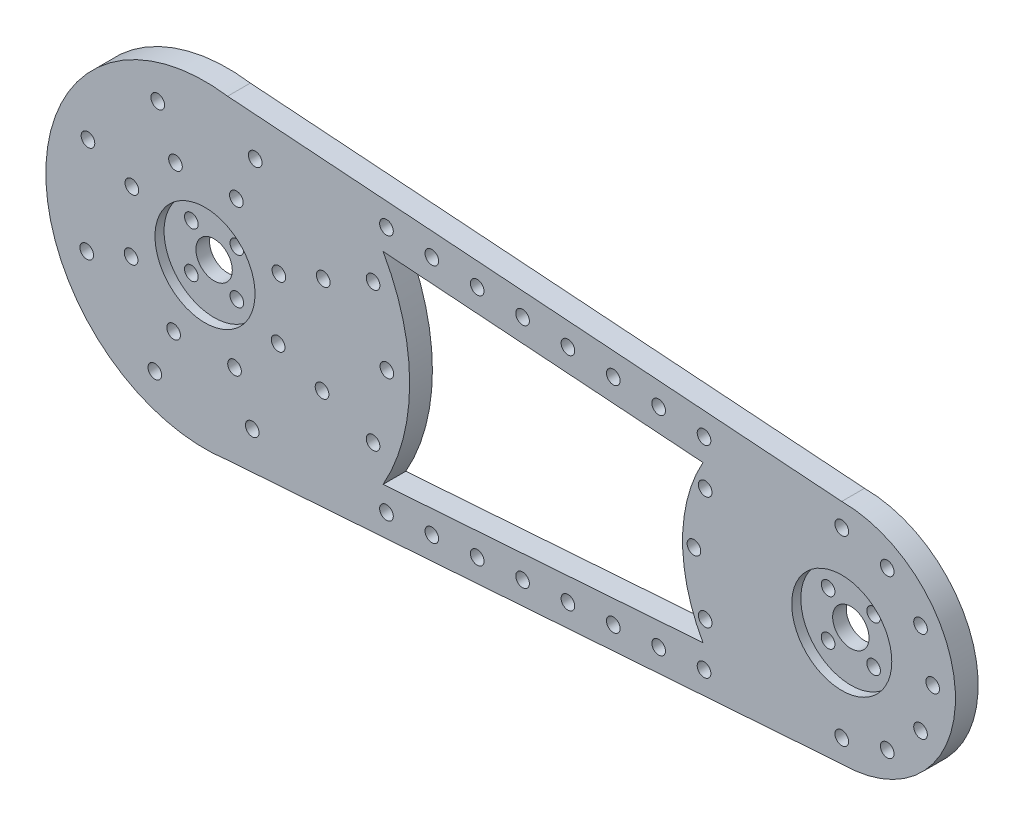
SolidWorks part; units mm, degrees
ref_plane "前视基准面" through (0, 0, 0) normal (0, 0, 1) x (1, 0, 0)
ref_plane "上视基准面" through (0, 0, 0) normal (0, 1, 0) x (1, 0, 0)
ref_plane "右视基准面" through (0, 0, 0) normal (1, 0, 0) x (0, 0, -1)
other "Configuration Table"
sketch "草图1" plane through (0, 0, 0) normal (0, 0, 1) x (1, 0, 0)
  line L0 (0, 0) -> (140, 0)
  line L1 (0, 35) -> (140, 25)
  line L2 (0, -35) -> (140, -25)
  circle A0 centre (0, 0) radius 35
  circle A1 centre (140, 0) radius 25
  dimension "D1" = 70
  dimension "D3" = 50
  dimension "D2" = 140
extrude "凸台-拉伸3" add sketch "草图1" along normal blind 5
sketch "草图4" plane through (0, 0, 5) normal (0, 0, 1) x (1, 0, 0)
  line L1 (-5, -5) -> (5, -5)
  line L2 (-5, -5) -> (-5, 5)
  line L3 (-5, 5) -> (5, 5)
  line L4 (5, -5) -> (5, 5)
  line L5 (-5, -5) -> (5, 5) construction
  line L6 (-5, 5) -> (5, -5) construction
  line L7 (135, -5) -> (145, -5)
  line L8 (135, -5) -> (135, 5)
  line L9 (135, 5) -> (145, 5)
  line L10 (145, -5) -> (145, 5)
  line L11 (135, -5) -> (145, 5) construction
  line L12 (135, 5) -> (145, -5) construction
  circle A0 centre (0, 0) radius 4
  circle A1 centre (-5, 5) radius 1.5
  circle A2 centre (5, 5) radius 1.5
  circle A3 centre (5, -5) radius 1.5
  circle A4 centre (-5, -5) radius 1.5
  circle A5 centre (140, 0) radius 4
  circle A6 centre (135, 5) radius 1.5
  circle A7 centre (145, 5) radius 1.5
  circle A8 centre (145, -5) radius 1.5
  circle A9 centre (135, -5) radius 1.5
  dimension "D1" = 8
  dimension "D4" = 3
  dimension "D6" = 8
  dimension "D9" = 3
  dimension "D2" = 10
  dimension "D3" = 10
  dimension "D7" = 10
  dimension "D8" = 10
  dimension "D5" = 4
  dimension "D10" = 4
extrude "切除-拉伸3" cut sketch "草图4" against normal blind 5 contours A5 | A0 | L2 A4 L1 | L1 A4 L2 | A6 | A9 | A8 | A7 | A1 | A2 | A3
sketch "草图5" plane through (0, 0, 5) normal (0, 0, 1) x (1, 0, 0)
  circle A0 centre (0, 0) radius 11
  circle A1 centre (140, 0) radius 11
  dimension "D1" = 22
  dimension "D2" = 22
extrude "切除-拉伸4" cut sketch "草图5" against normal blind 2
sketch "草图6" plane through (0, 0, 5) normal (0, 0, 1) x (1, 0, 0)
  circle A0 centre (0, 0) radius 30
  circle A1 centre (0, 30) radius 1.5
  circle A2 centre (15, 25.9808) radius 1.5
  circle A3 centre (25.9808, 15) radius 1.5
  circle A4 centre (30, 0) radius 1.5
  circle A5 centre (25.9808, -15) radius 1.5
  circle A6 centre (15, -25.9808) radius 1.5
  circle A7 centre (0, -30) radius 1.5
  circle A8 centre (-15, -25.9808) radius 1.5
  circle A9 centre (-25.9808, -15) radius 1.5
  circle A10 centre (-30, 0) radius 1.5
  circle A11 centre (-25.9808, 15) radius 1.5
  circle A12 centre (-15, 25.9808) radius 1.5
  circle A13 centre (140, 0) radius 20
  circle A14 centre (140, 20) radius 1.5
  circle A15 centre (150, 17.3205) radius 1.5
  circle A16 centre (157.3205, 10) radius 1.5
  circle A17 centre (160, 0) radius 1.5
  circle A18 centre (157.3205, -10) radius 1.5
  circle A19 centre (150, -17.3205) radius 1.5
  circle A20 centre (140, -20) radius 1.5
  circle A21 centre (130, -17.3205) radius 1.5
  circle A22 centre (122.6795, -10) radius 1.5
  circle A23 centre (120, 0) radius 1.5
  circle A24 centre (122.6795, 10) radius 1.5
  circle A25 centre (130, 17.3205) radius 1.5
  point P29 (0, 0)
  dimension "D1" = 60
  dimension "D2" = 3
  dimension "D4" = 40
  dimension "D5" = 3
  dimension "D3" = 12
  dimension "D6" = 12
extrude "切除-拉伸6" cut sketch "草图6" against normal through all contours A0 A12 | A11 | A1 | A2 | A3 | A4 | A5 | A6 | A7 | A8 | A9 | A10 | A25 | A14 | A15 | A16 | A17 | A18 | A19 | A20 | A21 | A22 | A23 | A24
sketch "草图8" plane through (0, 0, 5) normal (0, 0, 1) x (1, 0, 0)
  line L4 (-0.1715, -29.9995) -> (139.8316, -19.9993)
  line L5 (139.8316, 19.9993) -> (-0.1715, 29.9995)
  line L6 (-0.1715, -29.9995) -> (139.8316, -19.9993)
  line L7 (139.8316, 19.9993) -> (-0.1715, 29.9995)
  line L8 (-0.7125, 25.0254) -> (139.2875, 15.0254)
  line L9 (-0.7125, 25.0254) -> (139.2875, 15.0254)
  line L11 (-0.7125, -25.0254) -> (139.2875, -15.0254)
  line L12 (-0.7125, -25.0254) -> (139.2875, -15.0254)
  circle A3 centre (0, 30) radius 1.5
  arc A4 (139.8316, -19.9993) -> (139.8316, 19.9993) centre (140, 0) ccw
  arc A5 (-0.1715, 29.9995) -> (-0.1715, -29.9995) centre (0, 0) ccw
  arc A6 (139.8316, -19.9993) -> (139.8316, 19.9993) centre (140, 0) ccw
  arc A7 (-0.1715, 29.9995) -> (-0.1715, -29.9995) centre (0, 0) ccw
  circle A8 centre (9.9746, 29.2875) radius 1.5
  circle A9 centre (19.9492, 28.5751) radius 1.5
  circle A10 centre (29.9238, 27.8626) radius 1.5
  circle A11 centre (39.8983, 27.1501) radius 1.5
  circle A12 centre (49.8729, 26.4376) radius 1.5
  circle A13 centre (59.8475, 25.7252) radius 1.5
  circle A14 centre (69.8221, 25.0127) radius 1.5
  circle A15 centre (79.7967, 24.3002) radius 1.5
  circle A16 centre (89.7713, 23.5878) radius 1.5
  circle A17 centre (99.7459, 22.8753) radius 1.5
  circle A18 centre (109.7205, 22.1628) radius 1.5
  circle A19 centre (119.695, 21.4504) radius 1.5
  circle A20 centre (129.6696, 20.7379) radius 1.5
  circle A21 centre (0, -30) radius 1.5
  circle A22 centre (9.9746, -29.2875) radius 1.5
  circle A23 centre (19.9492, -28.5751) radius 1.5
  circle A24 centre (29.9238, -27.8626) radius 1.5
  circle A25 centre (39.8983, -27.1501) radius 1.5
  circle A26 centre (49.8729, -26.4376) radius 1.5
  circle A27 centre (59.8475, -25.7252) radius 1.5
  circle A28 centre (69.8221, -25.0127) radius 1.5
  circle A29 centre (79.7967, -24.3002) radius 1.5
  circle A30 centre (89.7713, -23.5878) radius 1.5
  circle A31 centre (99.7459, -22.8753) radius 1.5
  circle A32 centre (109.7205, -22.1628) radius 1.5
  circle A33 centre (119.695, -21.4504) radius 1.5
  circle A34 centre (129.6696, -20.7379) radius 1.5
  circle A35 centre (0, 0) radius 35
  circle A36 centre (140, 0) radius 25
  dimension "D2" = 14
  dimension "D1" = 5
  dimension "D4" = 10
  dimension "D5" = 10
  dimension "D3" = 14
extrude "切除-拉伸8" cut sketch "草图8" against normal through all contours A36 L9 A35 L12 | L6 A25 | L6 A25 | A8 | A9 | A10 | A11 | A12 | A13 | A14 | A16 | A15 | A17 | A18 | A19 | A20 | A34 | A33 | A32 | A31 | A30 | A29 | A28 | A27 | A26 | A24 | A23 | A22
sketch "草图9" plane through (0, 0, 5) normal (0, 0, 1) x (1, 0, 0)
  circle A0 centre (15, 25.9808) radius 1.5
  circle A1 centre (15, -25.9808) radius 1.5
extrude "凸台-拉伸4" add sketch "草图9" against normal blind 5
sketch "草图10" plane through (0, 0, 5) normal (0, 0, 1) x (1, 0, 0)
  circle A0 centre (130, -17.3205) radius 1.5
  circle A1 centre (130, 17.3205) radius 1.5
extrude "凸台-拉伸6" add sketch "草图10" against normal blind 5
sketch "草图11" plane through (0, 0, 5) normal (0, 0, 1) x (1, 0, 0)
  circle A0 centre (25.9808, -15) radius 1.5
  circle A1 centre (30, 0) radius 1.5
  circle A2 centre (25.9808, 15) radius 1.5
  circle A3 centre (122.6795, -10) radius 1.5
  circle A4 centre (120, 0) radius 1.5
  circle A5 centre (122.6795, 10) radius 1.5
  circle A6 centre (119.695, 21.4504) radius 1.5
  circle A7 centre (119.695, -21.4504) radius 1.5
  circle A8 centre (29.9238, -27.8626) radius 1.5
  circle A9 centre (29.9238, 27.8626) radius 1.5
  circle A10 centre (0, 0) radius 11
  circle A11 centre (0, 0) radius 35
  circle A12 centre (19.9492, -28.5751) radius 1.5
  circle A13 centre (19.9492, 28.5751) radius 1.5
  circle A14 centre (140, 0) radius 11
  circle A15 centre (140, 0) radius 24.9365
  circle A16 centre (129.6696, -20.7379) radius 1.5
  circle A17 centre (129.6696, 20.7379) radius 1.5
extrude "凸台-拉伸12" add sketch "草图11" against normal blind 5 contours A16 | A7 | A6 | A13 A11 A12 A0 A1 A2 A10 | A1 | A2 | A11 A13 | A11 A13 | A9 | A8 | A17
sketch "草图14" plane through (0, 0, 0) normal (0, 0, -1) x (-1, 0, 0)
  circle A2 centre (-11.0396, 25.7318) radius 1.5
  circle A3 centre (-6.8997, 16.0824) radius 1.5
  circle A4 centre (6.4931, 16.2508) radius 1.5
  circle A5 centre (10.389, 26.0013) radius 1.5
  circle A6 centre (16.0824, 6.8997) radius 1.5
  circle A7 centre (25.7318, 11.0396) radius 1.5
  circle A8 centre (16.2508, -6.4931) radius 1.5
  circle A9 centre (26.0013, -10.389) radius 1.5
  circle A10 centre (6.8997, -16.0824) radius 1.5
  circle A11 centre (11.0396, -25.7318) radius 1.5
  circle A12 centre (-6.4931, -16.2508) radius 1.5
  circle A13 centre (-10.389, -26.0013) radius 1.5
  circle A14 centre (-16.0824, -6.8997) radius 1.5
  circle A15 centre (-25.7318, -11.0396) radius 1.5
  circle A16 centre (-16.2508, 6.4931) radius 1.5
  circle A17 centre (-26.0013, 10.389) radius 1.5
  point P41 (0, 0)
  dimension "D1" = 8
extrude "切除-拉伸9" cut sketch "草图14" against normal blind 5
sketch "草图15" plane through (0, 0, 0) normal (0, 0, -1) x (-1, 0, 0)
  line L0 (-26.2977, -23.0961) -> (-32.9913, -22.618)
  line L1 (-26.2977, -23.0961) -> (-121.0676, -16.3268) construction
  line L2 (-26.2977, 23.0961) -> (-32.9913, 22.618)
  line L3 (-26.2977, 23.0961) -> (-121.0676, 16.3268) construction
  circle A0 centre (0, 0) radius 35
  circle A1 centre (0, 0) radius 40
  dimension "D1" = 80
extrude "凸台-拉伸13" add sketch "草图15" against normal blind 5 contours L2 A1 L0 A0
sketch "草图16" plane through (0, 0, 0) normal (0, 0, -1) x (-1, 0, 0)
  circle A1 centre (-35, 0) radius 1.5
  circle A2 centre (-32.3358, 13.3939) radius 1.5
  circle A16 centre (-32.3358, -13.3939) radius 1.5
  circle A17 centre (-24.7487, 24.7487) radius 1.5 [skipped]
  circle A18 centre (-24.7487, -24.7487) radius 1.5 [skipped]
  circle A19 centre (-13.3939, -32.3358) radius 1.5 [skipped]
  circle A20 centre (-13.3939, 32.3358) radius 1.5 [skipped]
  circle A21 centre (0, 35) radius 1.5 [skipped]
  circle A22 centre (13.3939, 32.3358) radius 1.5 [skipped]
  circle A23 centre (24.7487, 24.7487) radius 1.5 [skipped]
  circle A24 centre (32.3358, 13.3939) radius 1.5 [skipped]
  circle A25 centre (35, 0) radius 1.5 [skipped]
  circle A26 centre (32.3358, -13.3939) radius 1.5 [skipped]
  circle A27 centre (24.7487, -24.7487) radius 1.5 [skipped]
  circle A28 centre (13.3939, -32.3358) radius 1.5 [skipped]
  circle A29 centre (0, -35) radius 1.5 [skipped]
  dimension "D1" = 3
  dimension "D2" = 16
extrude "切除-拉伸10" cut sketch "草图16" against normal blind 5
sketch "草图18" plane through (0, 0, 5) normal (0, 0, 1) x (1, 0, 0)
  line L0 (32.9913, 22.618) -> (39.1555, 22.1777)
  line L1 (32.9913, 22.618) -> (121.0676, 16.3268) construction
  line L2 (32.9913, -22.618) -> (39.1555, -22.1777)
  line L3 (32.9913, -22.618) -> (121.0676, -16.3268) construction
  circle A0 centre (0, 0) radius 40
  circle A1 centre (0, 0) radius 45
  dimension "D1" = 90
extrude "凸台-拉伸14" add sketch "草图18" against normal blind 5 contours L2 A1 L0 A0
sketch "草图19" plane through (0, 0, 5) normal (0, 0, 1) x (1, 0, 0)
  circle A0 centre (32.3358, 13.3939) radius 1.5
  circle A1 centre (35, 0) radius 1.5
  circle A2 centre (32.3358, -13.3939) radius 1.5
extrude "凸台-拉伸15" add sketch "草图19" against normal blind 5
sketch "草图20" plane through (0, 0, 0) normal (0, 0, -1) x (-1, 0, 0)
  circle A1 centre (-40, 0) radius 1.5
  circle A2 centre (-36.9552, 15.3073) radius 1.5
  circle A4 centre (-15.3073, 36.9552) radius 1.5
  circle A5 centre (0, 40) radius 1.5
  circle A6 centre (15.3073, 36.9552) radius 1.5
  circle A7 centre (28.2843, 28.2843) radius 1.5
  circle A8 centre (36.9552, 15.3073) radius 1.5
  circle A9 centre (40, 0) radius 1.5
  circle A10 centre (36.9552, -15.3073) radius 1.5
  circle A11 centre (28.2843, -28.2843) radius 1.5
  circle A12 centre (15.3073, -36.9552) radius 1.5
  circle A13 centre (0, -40) radius 1.5
  circle A14 centre (-15.3073, -36.9552) radius 1.5
  circle A16 centre (-36.9552, -15.3073) radius 1.5
  circle A17 centre (-28.2843, -28.2843) radius 1.5 [skipped]
  circle A18 centre (-28.2843, 28.2843) radius 1.5 [skipped]
  point P38 (0, 0)
  dimension "D2" = 3
  dimension "D3" = 16
extrude "切除-拉伸11" cut sketch "草图20" against normal blind 5
sketch "草图21" plane through (0, 0, 0) normal (0, 0, -1) x (-1, 0, 0)
  line L0 (-121.0676, 16.3268) -> (-115.113, 16.7522)
  line L1 (-39.1555, 22.1777) -> (-121.0676, 16.3268) construction
  line L2 (-121.0676, -16.3268) -> (-115.113, -16.7522)
  line L3 (-39.1555, -22.1777) -> (-121.0676, -16.3268) construction
  circle A0 centre (-140, 0) radius 25
  circle A1 centre (-140, 0) radius 27.5
  circle A2 centre (-140, 0) radius 30
  dimension "D1" = 50
  dimension "D2" = 55
  dimension "D3" = 60
extrude "凸台-拉伸16" add sketch "草图21" against normal blind 5 contours L2 A1 L0 A0 | L2 A2 L0 A1
sketch "草图22" plane through (0, 0, 5) normal (0, 0, 1) x (1, 0, 0)
  circle A1 centre (122.6795, 10) radius 1.5
  circle A2 centre (120, 0) radius 1.5
  circle A3 centre (122.6795, -10) radius 1.5
extrude "凸台-拉伸17" add sketch "草图22" against normal blind 5
sketch "草图23" plane through (0, 0, 5) normal (0, 0, 1) x (1, 0, 0)
  circle A0 centre (140, 0) radius 27.5
  circle A1 centre (112.5, 0) radius 1.5
  circle A2 centre (116.1843, 13.75) radius 1.5
  circle A4 centre (140, 27.5) radius 1.5
  circle A5 centre (153.75, 23.8157) radius 1.5
  circle A6 centre (163.8157, 13.75) radius 1.5
  circle A7 centre (167.5, 0) radius 1.5
  circle A8 centre (163.8157, -13.75) radius 1.5
  circle A9 centre (153.75, -23.8157) radius 1.5
  circle A10 centre (140, -27.5) radius 1.5
  circle A12 centre (116.1843, -13.75) radius 1.5
  circle A13 centre (126.25, 23.8157) radius 1.5 [skipped]
  circle A14 centre (126.25, -23.8157) radius 1.5 [skipped]
  dimension "D1" = 55
  dimension "D2" = 3
  dimension "D3" = 12
extrude "切除-拉伸15" cut sketch "草图23" against normal blind 5 contours A0 A2 | A0 A12 | A0 A12 | A1
sketch "草图24" plane through (0, 0, 5) normal (0, 0, 1) x (1, 0, 0)
  circle A0 centre (116.1843, 13.75) radius 1.5
  circle A1 centre (112.5, 0) radius 1.5
  circle A2 centre (116.1843, -13.75) radius 1.5
extrude "凸台-拉伸21" add sketch "草图24" against normal blind 5
sketch "草图29" plane through (0, 0, 5) normal (0, 0, 1) x (1, 0, 0)
  line L0 (115.113, 16.7522) -> (109.4918, 17.1537)
  line L1 (39.1555, 22.1777) -> (115.113, 16.7522) construction
  line L2 (115.113, -16.7522) -> (109.4918, -17.1537)
  line L3 (39.1555, -22.1777) -> (115.113, -16.7522) construction
  circle A0 centre (140, 0) radius 35
  circle A1 centre (140, 0) radius 30
  circle A2 centre (140, 0) radius 32.5
  circle A3 centre (107.5, 0) radius 1.5
  circle A4 centre (109.9739, 12.4372) radius 1.5
  circle A5 centre (117.019, 22.981) radius 1.5
  circle A6 centre (127.5628, 30.0261) radius 1.5
  circle A7 centre (140, 32.5) radius 1.5
  circle A8 centre (152.4372, 30.0261) radius 1.5
  circle A9 centre (162.981, 22.981) radius 1.5
  circle A10 centre (170.0261, 12.4372) radius 1.5
  circle A11 centre (172.5, 0) radius 1.5
  circle A12 centre (170.0261, -12.4372) radius 1.5
  circle A13 centre (162.981, -22.981) radius 1.5
  circle A14 centre (152.4372, -30.0261) radius 1.5
  circle A15 centre (140, -32.5) radius 1.5
  circle A16 centre (127.5628, -30.0261) radius 1.5
  circle A17 centre (117.019, -22.981) radius 1.5
  circle A18 centre (109.9739, -12.4372) radius 1.5
  dimension "D1" = 70
  dimension "D2" = 65
  dimension "D3" = 3
  dimension "D4" = 16
extrude "凸台-拉伸22" add sketch "草图29" against normal blind 5 contours A18 A2 L2 A1 L0 A4 A3 | A18 A2 A3 A4 L0 A0 L2
